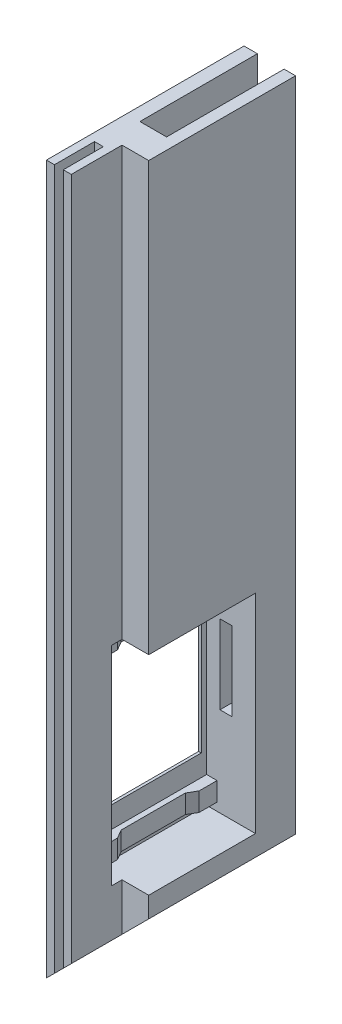
SolidWorks part; units mm, degrees
ref_plane "Front Plane" through (0, 0, 0) normal (0, 0, 1) x (1, 0, 0)
ref_plane "Top Plane" through (0, 0, 0) normal (0, 1, 0) x (1, 0, 0)
ref_plane "Right Plane" through (0, 0, 0) normal (1, 0, 0) x (0, 0, -1)
sketch "Sketch1" plane through (0, 0, 0) normal (0, 1, 0) x (1, 0, 0)
  line L2 (-51.5058, 37) -> (-32.2058, 37)
  line L3 (-32.2058, -18) -> (-42.2058, -18)
  line L4 (-42.2058, -18) -> (-42.2058, -37)
  line L5 (-42.2058, -37) -> (-45.2058, -37)
  line L6 (-45.2058, -37) -> (-45.2058, -22)
  line L7 (-45.2058, -22) -> (-48.5058, -22)
  line L8 (-48.5058, -22) -> (-48.5058, -37)
  line L9 (-48.5058, -37) -> (-51.5058, -37)
  line L10 (-51.5058, -37) -> (-51.5058, 37)
  line L11 (-32.2058, 37) -> (-32.2058, -18)
extrude "Boss-Extrude1" add sketch "Sketch1" along normal blind 265.3
sketch "Sketch2" plane through (0, 265.3, 0) normal (0, 1, 0) x (1, 0, 0)
  line L0 (-46.5058, 37) -> (-36.5058, 37)
  line L1 (-36.5058, 37) -> (-36.5058, -7)
  line L2 (-36.5058, -7) -> (-46.5058, -7)
  line L3 (-46.5058, -7) -> (-46.5058, 37)
  line L4 (-32.2058, 37) -> (-51.5058, 37) construction
  line L5 (-32.2058, -18) -> (-32.2058, 37) construction
  dimension "D1" = 44
  dimension "D2" = 10
  dimension "D3" = 4.3
extrude "Cut-Extrude1" cut sketch "Sketch2" against normal blind 10
ref_plane "Plane1" through (-25.7529, 25.7529, 0) normal (0.7071, -0.7071, 0) x (0, 0, 1)
sketch "Sketch3" plane through (-25.7529, 25.7529, 0) normal (0.7071, -0.7071, 0) x (0, 0, 1)
  line L1 (-132.4991, -59.9961) -> (138.6503, -59.9961)
  line L2 (-132.4991, -59.9961) -> (-132.4991, 99.0438)
  line L3 (-132.4991, 99.0438) -> (138.6503, 99.0438)
  line L4 (138.6503, -59.9961) -> (138.6503, 99.0438)
  line L5 (-132.4991, -59.9961) -> (138.6503, 99.0438) construction
  line L6 (-132.4991, 99.0438) -> (138.6503, -59.9961) construction
  point P0 (3.0756, 19.5239)
extrude "Cut-Extrude2" cut sketch "Sketch3" along normal blind 31
sketch "Sketch4" plane through (-25.7529, 25.7529, 0) normal (0.7071, -0.7071, 0) x (0, 0, -1)
  line L0 (-18, -9.1258) -> (37, -9.1258) construction
  line L1 (25, -22.1258) -> (-3, -22.1258)
  line L2 (25, -22.1258) -> (25, -15.1258)
  line L3 (25, -15.1258) -> (-3, -15.1258)
  line L4 (-3, -22.1258) -> (-3, -15.1258)
  line L5 (37, -9.1258) -> (37, -36.4201) construction
  dimension "D1" = 28
  dimension "D2" = 7
  dimension "D3" = 6
  dimension "D4" = 12
extrude "Cut-Extrude3" cut sketch "Sketch4" against normal blind 8
sketch "Sketch5" plane through (-25.7529, 25.7529, 0) normal (0.7071, -0.7071, 0) x (0, 0, -1)
  line L0 (-3, -15.1258) -> (-3, -22.1258) construction
  line L1 (25.2, -22.3258) -> (-3.2, -22.3258)
  line L2 (25.2, -22.3258) -> (25.2, -14.9258)
  line L3 (25.2, -14.9258) -> (-3.2, -14.9258)
  line L4 (-3.2, -22.3258) -> (-3.2, -14.9258)
  line L5 (25, -22.1258) -> (25, -15.1258) construction
  line L6 (25, -15.1258) -> (-3, -15.1258) construction
  line L7 (-3, -22.1258) -> (25, -22.1258) construction
  dimension "D1" = 0.2
  dimension "D2" = 0.2
  dimension "D3" = 0.2
  dimension "D4" = 0.2
extrude "Cut-Extrude4" cut sketch "Sketch5" against normal up to surface (8 mm away) up to face at (-44.5802, 18.2393, -11)
sketch "Sketch6" plane through (-32.2058, 0, 0) normal (1, 0, 0) x (0, 0, -1)
  line L0 (37, 265.3) -> (37, 19.3) construction
  line L1 (22, 27) -> (-22, 27)
  line L2 (22, 27) -> (22, 105)
  line L3 (22, 105) -> (-22, 105)
  line L4 (-22, 27) -> (-22, 105)
  line L5 (-18, 19.3) -> (37, 19.3) construction
  dimension "D1" = 15
  dimension "D2" = 7.7
  dimension "D3" = 44
  dimension "D4" = 78
extrude "Cut-Extrude5" cut sketch "Sketch6" against normal blind 18.3
sketch "Sketch7" plane through (-50.5058, 0, 0) normal (1, 0, 0) x (0, 0, -1)
  line L0 (22, 27) -> (22, 105) construction
  line L1 (20, 45) -> (-20, 45)
  line L2 (20, 45) -> (20, 96)
  line L3 (20, 96) -> (-20, 96)
  line L4 (-20, 45) -> (-20, 96)
  line L5 (22, 105) -> (-18, 105) construction
  line L6 (-22, 105) -> (-22, 27) construction
  line L7 (-22, 27) -> (22, 27) construction
  dimension "D1" = 2
  dimension "D2" = 9
  dimension "D3" = 2
  dimension "D4" = 18
extrude "Cut-Extrude6" cut sketch "Sketch7" against normal blind 18.3
sketch "Sketch8" plane through (0, 0, -22) normal (0, 0, 1) x (1, 0, 0)
  line L0 (-50.5058, 27) -> (-32.2058, 27) construction
  line L1 (-50.5058, 30) -> (-46.6058, 30)
  line L2 (-50.5058, 30) -> (-50.5058, 37)
  line L3 (-50.5058, 37) -> (-46.6058, 37)
  line L4 (-46.6058, 30) -> (-46.6058, 37)
  line L5 (-50.5058, 27) -> (-50.5058, 105) construction
  dimension "D1" = 3
  dimension "D2" = 7
  dimension "D3" = 3.9
extrude "Boss-Extrude2" add sketch "Sketch8" along normal up to surface (44 mm away) up to face at (-43.7058, 66, 22)
sketch "Sketch10" plane through (0, 37, 0) normal (0, 1, 0) x (1, 0, 0)
  line L0 (-46.6058, -15.29) -> (-48.5058, -12.0014)
  line L1 (-46.6058, -22) -> (-46.6058, 22) construction
  line L2 (-48.5058, -12.0014) -> (-48.5058, 11.9986)
  line L3 (-48.5058, 11.9986) -> (-46.6058, 15.2872)
  line L4 (-46.6058, 15.2872) -> (-46.6058, -15.29)
  dimension "D1" = 1.9
  dimension "D2" = 3.798
  dimension "D3" = 24
  dimension "D4" = 6.71
extrude "Cut-Extrude7" cut sketch "Sketch10" against normal up to surface (7 mm away) up to face at (-48.5458, 30, 4.4)
pattern_linear "LPattern1" count 2 spacing 68 along (0, 1, 0) of "Cut-Extrude7", "Boss-Extrude2"
sketch "Sketch11" plane through (0, 0, -22) normal (0, 0, 1) x (1, 0, 0)
  line L0 (-50.5058, 27) -> (-32.2058, 27) construction
  line L1 (-41.0058, 60.5) -> (-45.5058, 60.5)
  line L2 (-41.0058, 60.5) -> (-41.0058, 90)
  line L3 (-41.0058, 90) -> (-45.5058, 90)
  line L4 (-45.5058, 60.5) -> (-45.5058, 90)
  line L5 (-32.2058, 27) -> (-32.2058, 105) construction
  dimension "D1" = 29.5
  dimension "D2" = 4.5
  dimension "D3" = 33.5
  dimension "D4" = 8.8
extrude "Cut-Extrude8" cut sketch "Sketch11" against normal up to surface (15 mm away) up to face at (-41.6808, 198.8875, -37)
